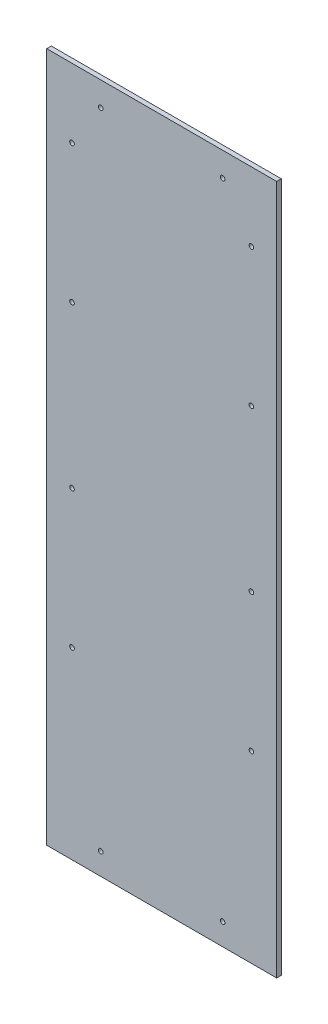
SolidWorks part; units mm, degrees
material "Alumina"
ref_plane "Front Plane" through (0, 0, 0) normal (0, 0, 1) x (1, 0, 0)
ref_plane "Top Plane" through (0, 0, 0) normal (0, 1, 0) x (1, 0, 0)
ref_plane "Right Plane" through (0, 0, 0) normal (1, 0, 0) x (0, 0, -1)
sketch "Sketch1" plane through (0, 0, 0) normal (0, 0, 1) x (1, 0, 0)
  line L1 (50, -150) -> (-50, -150)
  line L2 (50, -150) -> (50, 150)
  line L3 (50, 150) -> (-50, 150)
  line L4 (-50, -150) -> (-50, 150)
  line L5 (50, -150) -> (-50, 150) construction
  line L6 (50, 150) -> (-50, -150) construction
  point P0 (0, 0)
  dimension "D1" = 100
  dimension "D2" = 300
extrude "Boss-Extrude1" add sketch "Sketch1" along normal blind 2
sketch "Sketch2" plane through (0, 0, 2) normal (0, 0, 1) x (1, 0, 0)
  line L0 (-50, 150) -> (-50, -150) construction
  line L1 (50, 150) -> (-50, 150) construction
  line L3 (0, -1.1) -> (0, 1.1) construction
  circle A0 centre (-39, 120) radius 1
  circle A1 centre (-39, 60) radius 1
  circle A4 centre (-39, -10) radius 1
  circle A5 centre (-39, -70) radius 1
  circle A13 centre (39, -70) radius 1
  circle A14 centre (39, -10) radius 1
  circle A15 centre (39, 60) radius 1
  circle A16 centre (39, 120) radius 1
  dimension "D1" = 2
  dimension "D3" = 30
  dimension "D4" = 2
  dimension "D6" = 11
  dimension "D10" = 2
  dimension "D11" = 11
  dimension "D15" = 11
  dimension "D5" = 60
  dimension "D8" = 60
  dimension "D9" = 2
  dimension "D2" = 11
  dimension "D7" = 70
extrude "Cut-Extrude1" cut sketch "Sketch2" against normal blind 10
sketch "Sketch3" plane through (0, 0, 2) normal (0, 0, 1) x (1, 0, 0)
  line L0 (-26.5, 139.5) -> (26.5, 139.5) construction
  line L1 (26.5, 139.5) -> (26.5, -140.5) construction
  line L2 (26.5, -140.5) -> (-26.5, -140.5) construction
  line L3 (-26.5, -140.5) -> (-26.5, 139.5) construction
  line L4 (50, 150) -> (-50, 150) construction
  line L5 (-50, -150) -> (50, -150) construction
  line L6 (50, -150) -> (50, 150) construction
  line L7 (-50, 150) -> (-50, -150) construction
  circle A0 centre (-26.5, -140.5) radius 1
  circle A1 centre (26.5, -140.5) radius 1
  circle A2 centre (-26.5, 139.5) radius 1
  circle A3 centre (26.5, 139.5) radius 1
  dimension "D5" = 2
  dimension "D6" = 2
  dimension "D7" = 2
  dimension "D8" = 2
  dimension "D1" = 10.5
  dimension "D2" = 9.5
  dimension "D3" = 23.5
  dimension "D4" = 23.5
extrude "Cut-Extrude2" cut sketch "Sketch3" against normal blind 10
